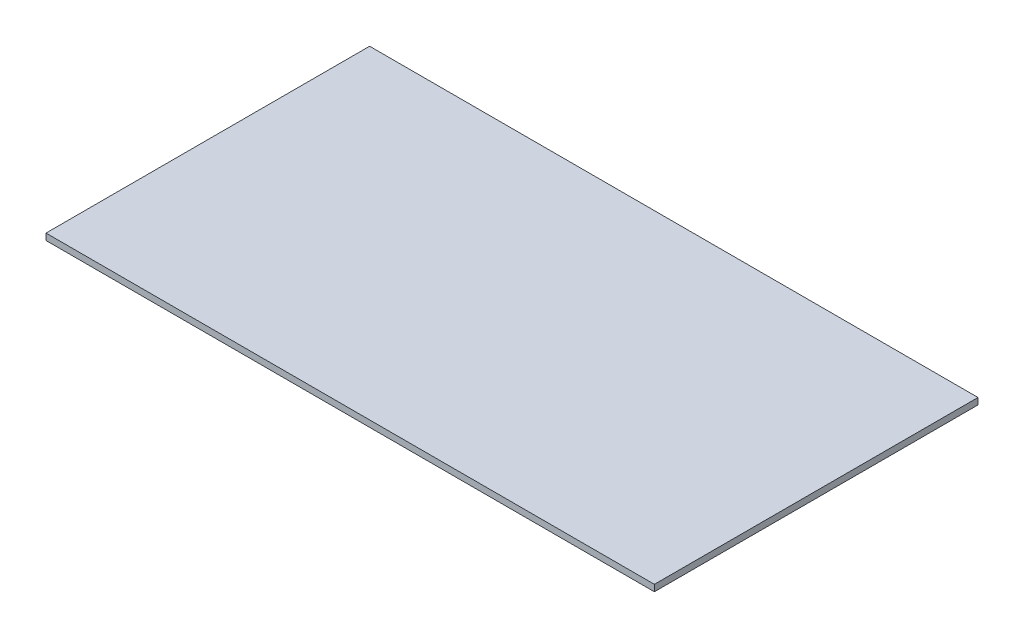
SolidWorks part; units mm, degrees
ref_plane "Front Plane" through (0, 0, 0) normal (0, 0, 1) x (1, 0, 0)
ref_plane "Top Plane" through (0, 0, 0) normal (0, 1, 0) x (1, 0, 0)
ref_plane "Right Plane" through (0, 0, 0) normal (1, 0, 0) x (0, 0, -1)
sketch "Sketch1" plane through (0, 0, 0) normal (0, 1, 0) x (1, 0, 0)
  line L1 (0, 0) -> (4700, 0)
  line L2 (0, 0) -> (0, 2500)
  line L3 (0, 2500) -> (4700, 2500)
  line L4 (4700, 0) -> (4700, 2500)
  dimension "D1" = 2500
  dimension "D2" = 4700
extrude "Boss-Extrude1" add sketch "Sketch1" along normal blind 50
